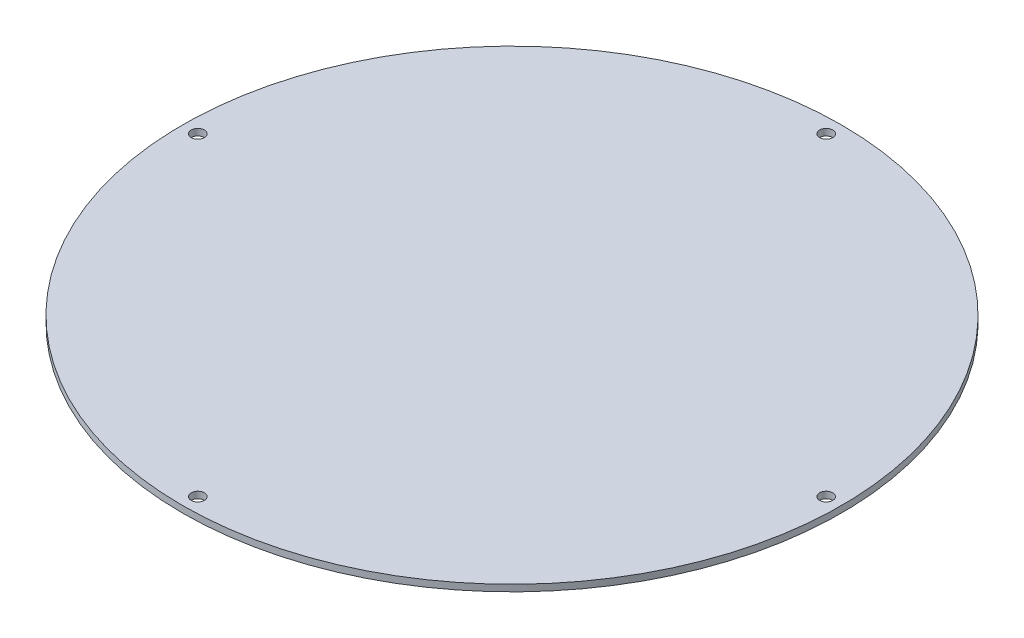
SolidWorks part; units mm, degrees
ref_plane "Front Plane" through (0, 0, 0) normal (0, 0, 1) x (1, 0, 0)
ref_plane "Top Plane" through (0, 0, 0) normal (0, 1, 0) x (1, 0, 0)
ref_plane "Right Plane" through (0, 0, 0) normal (1, 0, 0) x (0, 0, -1)
sketch "Sketch1" plane through (0, 0, 0) normal (0, 1, 0) x (1, 0, 0)
  line L0 (0, 87.139) -> (0, -119.2747) construction
  line L1 (-102.926, 0) -> (214.991, 0) construction
  circle A0 centre (0, 0) radius 75
  circle A2 centre (0, 71.5) radius 1.5
  circle A3 centre (71.5, 0) radius 1.5
  circle A4 centre (0, -71.5) radius 1.5
  circle A5 centre (-71.5, 0) radius 1.5
  dimension "D1" = 150
  dimension "D2" = 71.5
  dimension "D3" = 3
  dimension "D4" = 4
extrude "Boss-Extrude2" add sketch "Sketch1" along normal blind 1.5
